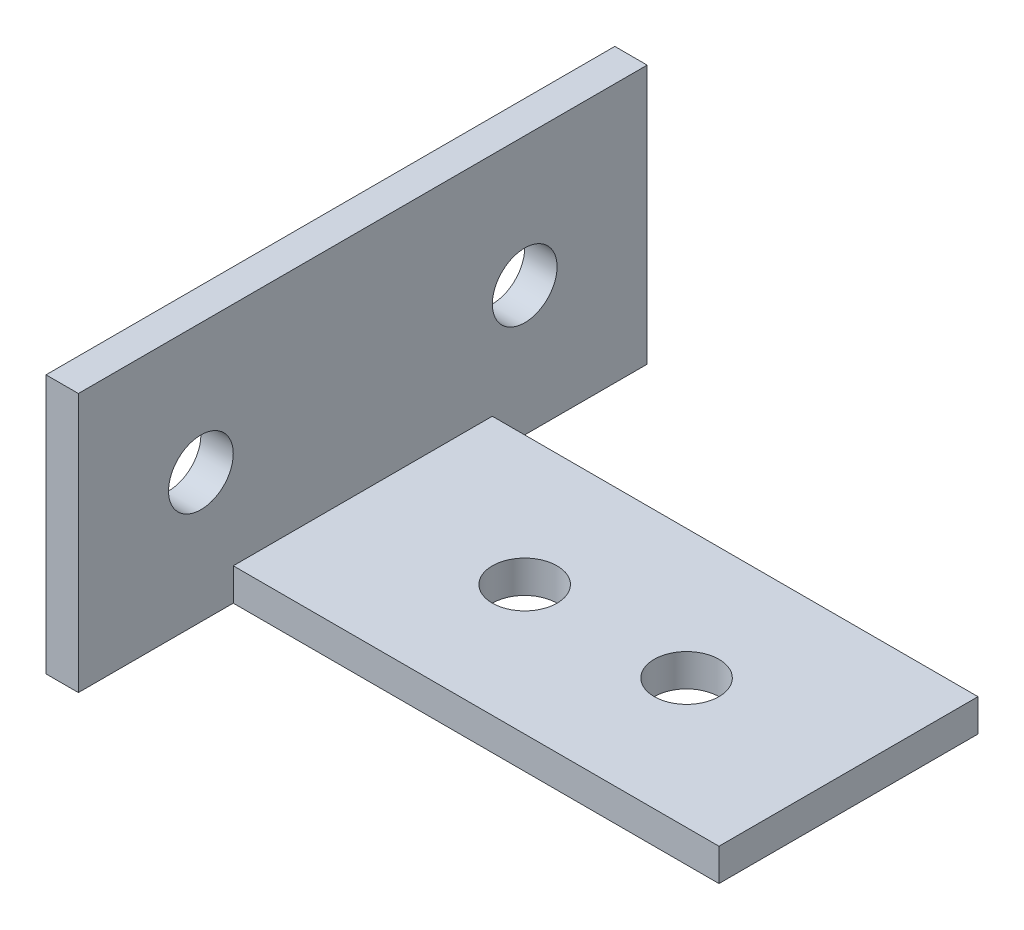
SolidWorks part; units mm, degrees
ref_plane "Front Plane" through (0, 0, 0) normal (0, 0, 1) x (1, 0, 0)
ref_plane "Top Plane" through (0, 0, 0) normal (0, 1, 0) x (1, 0, 0)
ref_plane "Right Plane" through (0, 0, 0) normal (1, 0, 0) x (0, 0, -1)
sketch "Sketch1" plane through (0, 0, 0) normal (1, 0, 0) x (0, 0, -1)
  line L0 (-15.875, 0) -> (15.875, 0)
  line L1 (0, 0) -> (0, 12.7)
  line L3 (-15.875, -12.7) -> (22.1168, -12.8275)
  line L4 (-27.8877, -12.7) -> (27.8877, -12.7)
  line L5 (0, 12.7) -> (-22.115, 12.7)
  line L6 (-27.8877, -12.7) -> (-27.8877, 12.7)
  line L7 (-15.875, 0) -> (-15.875, -12.7)
  line L8 (-27.8877, 12.7) -> (27.8877, 12.7)
  line L9 (15.875, 0) -> (15.875, 12.7)
  line L10 (27.8877, -12.7) -> (27.8877, 12.7)
  line L11 (27.8877, 12.7) -> (15.875, 12.7)
  line L13 (-27.8877, -12.7) -> (-15.875, -12.7)
  line L14 (-27.8877, -12.7) -> (-27.8877, 12.7)
  line L15 (-27.8877, 12.7) -> (-22.115, 12.7)
  line L16 (27.8877, 12.7) -> (27.8877, -12.7)
  line L17 (27.8877, -12.7) -> (22.115, -12.7)
  line L18 (22.115, -12.7) -> (22.1168, -12.8275)
  circle A0 centre (-15.875, 0) radius 3.175
  circle A1 centre (15.875, 0) radius 3.175
  circle A2 centre (-15.875, 0) radius 3.175
  circle A3 centre (15.875, 0) radius 3.175
extrude "Boss-Extrude3" add sketch "Sketch1" along normal blind 3.175 contours A0 L0 L1 L5 L8 L6 L4 L7 | A1 L9 L8 L1 L0 | A1 L0 A0 L7 L4 L10 L8 L9
sketch "Sketch3" plane through (3.175, 0, 0) normal (1, 0, 0) x (0, 0, -1)
  line L0 (22.115, -12.7) -> (182.0966, 215.7774)
  line L1 (140.4837, 244.915) -> (-39.9003, -12.7)
  line L2 (-12.7, -12.7) -> (-12.7, -9.525)
  line L3 (-15.875, 0) -> (15.875, 0)
  line L4 (-12.7, -9.525) -> (12.7, -9.525)
  line L5 (0, -12.7) -> (-12.7, -12.7)
  line L6 (0, -12.7) -> (0, 0)
  line L8 (-12.7, -12.7) -> (12.7, -12.7)
  line L9 (-12.7, -12.7) -> (-12.7, -9.525)
  line L10 (-12.7, -9.525) -> (12.7, -9.525)
  line L11 (12.7, -12.7) -> (12.7, -9.525)
  circle A0 centre (-15.875, 0) radius 3.175
  circle A1 centre (15.875, 0) radius 3.175
  line M7 (-27.8877, -12.7) -> (27.8877, -12.7)
extrude "Boss-Extrude4" add sketch "Sketch3" along normal blind 47.625 contours L6 L4 L2 M7 | L11 L4 L6 M7
sketch "Sketch4" plane through (0, -9.525, 0) normal (0, 1, 0) x (1, 0, 0)
  line L1 (3.175, -12.7) -> (3.175, 12.7) construction
  line L2 (50.8, -12.7) -> (50.8, 12.7) construction
  line L5 (50.8, 12.7) -> (3.175, 12.7) construction
  circle A0 centre (19.05, 0) radius 3.175
  circle A1 centre (34.925, 0) radius 3.175
  dimension "D1" = 6.35
  dimension "D2" = 6.35
  dimension "D3" = 15.875
  dimension "D4" = 15.875
  dimension "D5" = 12.7
extrude "Cut-Extrude1" cut sketch "Sketch4" against normal blind 16.256
